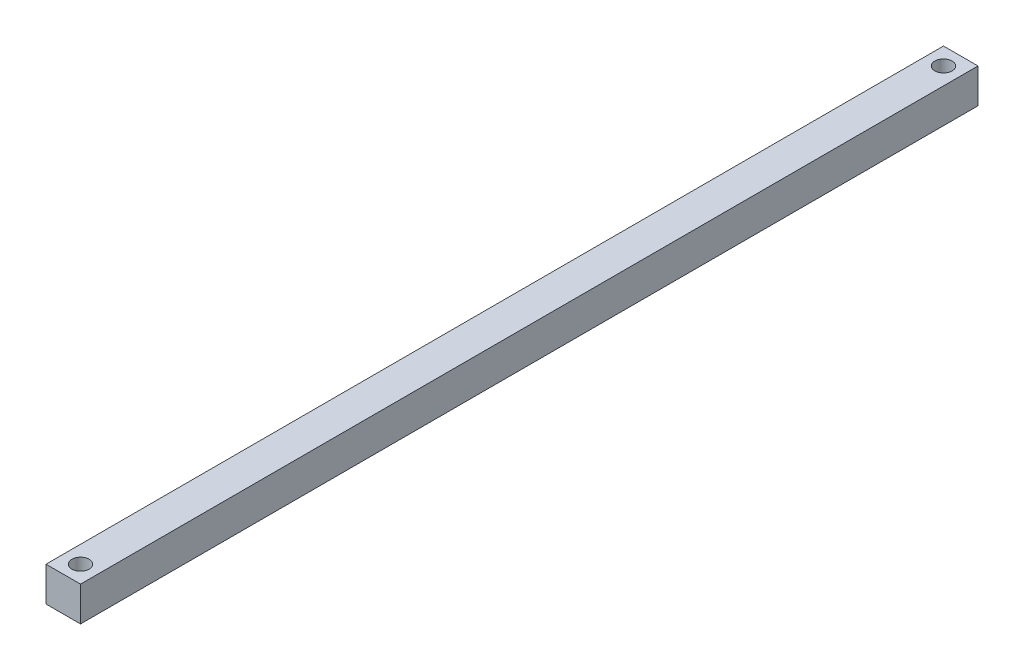
SolidWorks part; units mm, degrees
ref_plane "Plan de face" through (0, 0, 0) normal (0, 0, 1) x (1, 0, 0)
ref_plane "Plan de dessus" through (0, 0, 0) normal (0, 1, 0) x (1, 0, 0)
ref_plane "Plan de droite" through (0, 0, 0) normal (1, 0, 0) x (0, 0, -1)
sketch "Esquisse2" plane through (0, 0, 0) normal (0, 1, 0) x (1, 0, 0)
  line L1 (0, 0) -> (-10, 0)
  line L2 (0, 0) -> (0, 260)
  line L3 (0, 260) -> (-10, 260)
  line L4 (-10, 0) -> (-10, 260)
  dimension "D1" = 10
  dimension "D2" = 260
extrude "Boss.-Extru.1" add sketch "Esquisse2" along normal blind 10
sketch "Esquisse3" plane through (0, 10, 0) normal (0, 1, 0) x (1, 0, 0)
  line L0 (-5, 0) -> (-5, 260) construction
  line L1 (-10, 0) -> (0, 0) construction
  line L2 (0, 260) -> (-10, 260) construction
  circle A0 centre (-5, 255) radius 2.5
  circle A1 centre (-5, 5) radius 2.5
  dimension "D1" = 5
  dimension "D2" = 5
  dimension "D3" = 5
  dimension "D4" = 5
extrude "Enlèv. mat.-Extru.1" cut sketch "Esquisse3" against normal blind 10
sketch "Esquisse4" plane through (0, 0, 0) normal (0, -1, 0) x (-1, 0, 0)
  line L0 (0, 224) -> (10.6199, 224)
  line L1 (0, 0) -> (0, 260) construction
  dimension "D1" = 36
